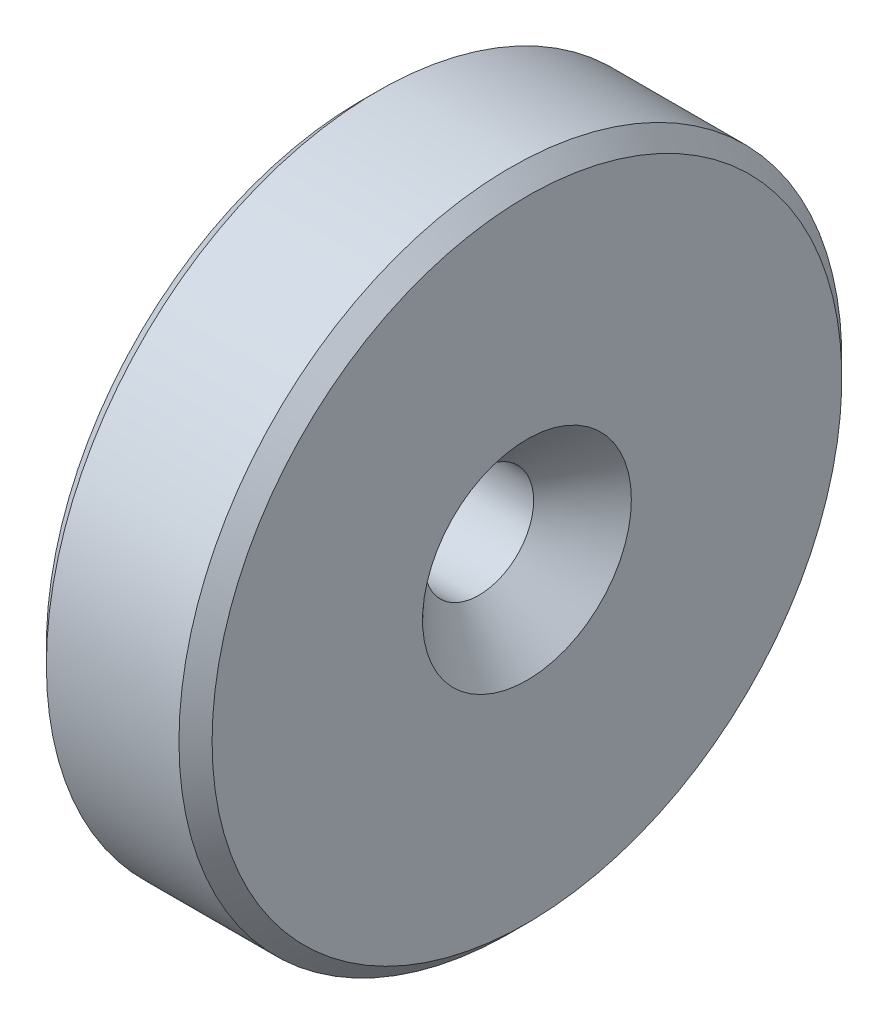
SolidWorks part; units mm, degrees
ref_plane "Plan1" through (0, 0, 0) normal (0, 0, 1) x (1, 0, 0)
ref_plane "Plan2" through (0, 0, 0) normal (0, 1, 0) x (1, 0, 0)
ref_plane "Plan3" through (0, 0, 0) normal (1, 0, 0) x (0, 0, -1)
sketch "Esquisse1" plane through (0, 0, 0) normal (0, 0, 1) x (1, 0, 0)
  line L0 (0, 0) -> (20, 0) construction
  line L2 (0, 0) -> (10, 0)
  line L3 (0, 0) -> (0, 20)
  line L4 (0, 20) -> (10, 20)
  line L5 (10, 0) -> (10, 20)
  dimension "D1" = 10
  dimension "D2" = 20
revolve "Base-Révolution" add sketch "Esquisse1" angle 360 about L0
chamfer "Chanfrein1" distance 1 angle 45 2 edges at (10, 0, 20) (0, 0, 20)
hole_wizard "Perçage1" positions "Esquisse3" profile "Esquisse2" countersink size "M6" standard "ISO" end condition through all
sketch "Esquisse3" plane through (10, 0, 0) normal (1, 0, 0) x (0, 0, -1)
  circle A0 centre (0, 0) radius 20 construction
  point P0 (0, 0)
sketch "Esquisse2" plane through (10, 0, 0) normal (0, 1, 0) x (0, 0, -1)
  line L0 (0, 0) -> (0, 10)
  line L1 (0, 10) -> (3.3, 10)
  line L2 (3.3, 10) -> (3.3, 2.8971)
  line L3 (3.3, 2.8971) -> (6.3, 0)
  line L5 (6.3, 0) -> (0, 0)
  line L6 (-3.3, 2.8971) -> (-6.3, 0) construction
  line L11 (0, -6.35) -> (0, 107.95) construction
  dimension "Diamètre du perçage jusqu'au prochain" = 6.6
  dimension "Profondeur du perçage jusqu'au prochain" = 10
  dimension "Diamètre du fraisage entrant" = 12.6
  dimension "Angle du fraisage entrant" = 92
sketch "Esquisse5" plane through (0, 0, 0) normal (0, 1, 0) x (1, 0, 0)
  line L0 (0, 0) -> (10, 0) construction
  line L2 (-2, 0.125) -> (0.1, 0.125)
  line L3 (-2, 0.125) -> (-2, -0.125)
  line L4 (-2, -0.125) -> (0.1, -0.125)
  line L5 (0.1, 0.125) -> (0.1, -0.125)
  dimension "D1" = 2
  dimension "D2" = 0.25
  dimension "D3" = 2.1
extrude "Enlèv. mat.-Extru.1" cut sketch "Esquisse5" against normal mid plane 40
